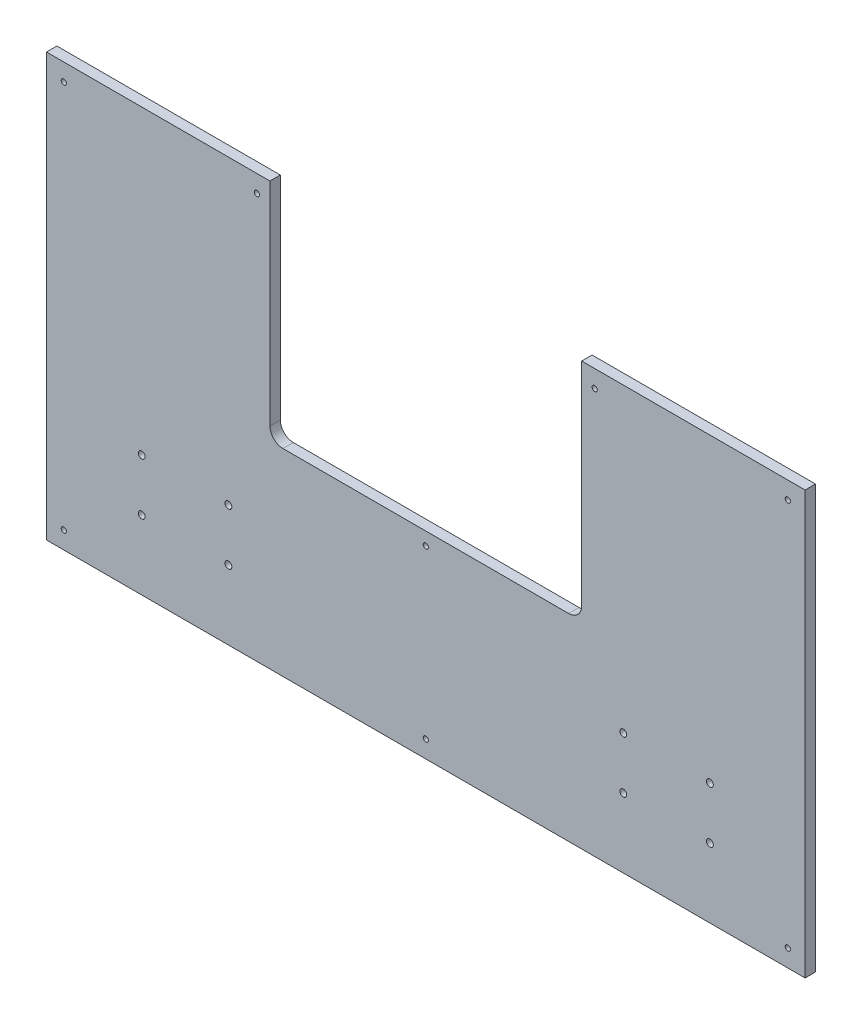
SolidWorks part; units mm, degrees
ref_plane "Спереди" through (0, 0, 0) normal (0, 0, 1) x (1, 0, 0)
ref_plane "Сверху" through (0, 0, 0) normal (0, 1, 0) x (1, 0, 0)
ref_plane "Справа" through (0, 0, 0) normal (1, 0, 0) x (0, 0, -1)
sketch "Эскиз1" plane through (0, 0, 0) normal (0, 0, 1) x (1, 0, 0)
  line L0 (129, 244) -> (129, 121.5)
  line L1 (0, 0) -> (438, 0)
  line L2 (0, 0) -> (0, 244)
  line L3 (0, 244) -> (438, 244) construction
  line L4 (438, 0) -> (438, 244)
  line L5 (136.5, 114) -> (301.5, 114)
  line L6 (309, 121.5) -> (309, 244)
  line L7 (0, 244) -> (129, 244)
  line L8 (309, 244) -> (438, 244)
  line L9 (55, 70) -> (105, 70) construction
  line L10 (333, 70) -> (383, 70) construction
  arc A0 (129, 121.5) -> (136.5, 114) centre (136.5, 121.5) ccw
  arc A1 (301.5, 114) -> (309, 121.5) centre (301.5, 121.5) ccw
  circle A2 centre (10, 10) radius 1.5
  circle A3 centre (10, 234) radius 1.5
  circle A4 centre (121.5, 234) radius 1.5
  circle A7 centre (316.5, 234) radius 1.5
  circle A8 centre (428, 234) radius 1.5
  circle A9 centre (428, 10) radius 1.5
  circle A10 centre (219, 106.5) radius 1.5
  circle A11 centre (219, 10) radius 1.5
  circle A12 centre (333, 70) radius 2
  circle A13 centre (383, 70) radius 2
  circle A14 centre (383, 40) radius 2
  circle A15 centre (333, 40) radius 2
  circle A16 centre (55, 70) radius 2
  circle A17 centre (105, 70) radius 2
  circle A18 centre (55, 40) radius 2
  circle A19 centre (105, 40) radius 2
  point P8 (219, 114)
  point P44 (80, 70)
  point P47 (358, 70)
  dimension "D6" = 15
  dimension "D7" = 15
  dimension "D8" = 3
  dimension "D9" = 3
  dimension "D10" = 3
  dimension "D11" = 3
  dimension "D12" = 3
  dimension "D13" = 3
  dimension "D14" = 3
  dimension "D15" = 3
  dimension "D27" = 4
  dimension "D28" = 4
  dimension "D29" = 4
  dimension "D30" = 4
  dimension "D31" = 4
  dimension "D32" = 4
  dimension "D33" = 4
  dimension "D34" = 4
  dimension "D1" = 438
  dimension "D2" = 244
  dimension "D3" = 130
  dimension "D4" = 180
  dimension "D5" = 219
  dimension "D16" = 7.5
  dimension "D17" = 10
  dimension "D18" = 10
  dimension "D19" = 10
  dimension "D20" = 7.5
  dimension "D21" = 7.5
  dimension "D22" = 10
  dimension "D23" = 50
  dimension "D24" = 50
  dimension "D25" = 80
  dimension "D26" = 30
  dimension "D35" = 80
  dimension "D36" = 40
extrude "Бобышка-Вытянуть1" add sketch "Эскиз1" along normal blind 6
